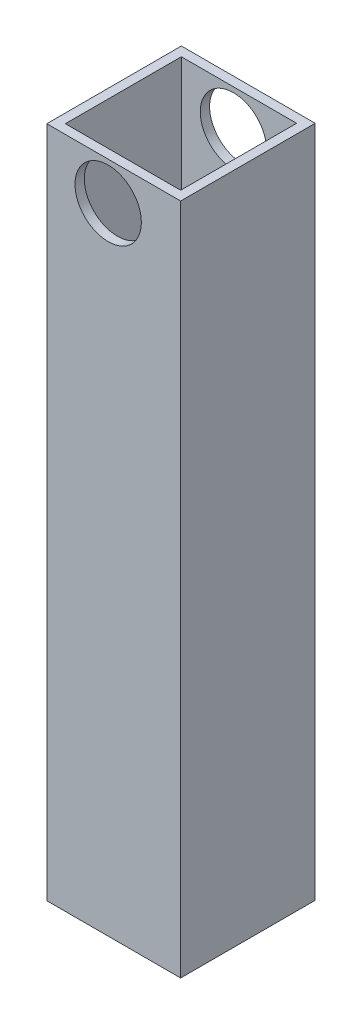
SolidWorks part; units mm, degrees
ref_plane "Front Plane" through (0, 0, 0) normal (0, 0, 1) x (1, 0, 0)
ref_plane "Top Plane" through (0, 0, 0) normal (0, 1, 0) x (1, 0, 0)
ref_plane "Right Plane" through (0, 0, 0) normal (1, 0, 0) x (0, 0, -1)
sketch "Sketch6" plane through (0, 0, 0) normal (0, 1, 0) x (1, 0, 0)
  line L0 (0, 0) -> (25.2621, 0)
  line L1 (25.2621, 0) -> (25.2621, 25.4)
  line L2 (25.2621, 25.4) -> (0, 25.4)
  line L3 (0, 25.4) -> (0, 0)
  dimension "D1" = 25.4
extrude "Boss-Extrude3" add sketch "Sketch6" along normal blind 127 contours L3 L0 L1 L2
sketch "Sketch8" plane through (0, 0, 0) normal (0, 0, 1) x (1, 0, 0)
  circle A1 centre (11.5872, 119.7801) radius 6.263
extrude "Cut-Extrude1" cut sketch "Sketch8" against normal blind 25.4
sketch "Sketch9" plane through (0, 0, 0) normal (0, -1, 0) x (-1, 0, 0)
  line L0 (0, 25.4) -> (0, 0) construction
  line L1 (-1.7526, 23.6474) -> (-23.5095, 23.6474)
  line L2 (-1.7526, 23.6474) -> (-1.7526, 1.7526)
  line L3 (-1.7526, 1.7526) -> (-23.5095, 1.7526)
  line L4 (-23.5095, 23.6474) -> (-23.5095, 1.7526)
  line L5 (-1.7526, 23.6474) -> (-23.5095, 1.7526) construction
  line L6 (-1.7526, 1.7526) -> (-23.5095, 23.6474) construction
  line L7 (-25.2621, 0) -> (-25.2621, 25.4) construction
  line L8 (-17.8502, 0) -> (-5.3242, 0) construction
  line L9 (-25.2621, 25.4) -> (0, 25.4) construction
  point P0 (-12.6311, 12.7)
  dimension "D1" = 1.7526
  dimension "D2" = 1.7526
  dimension "D3" = 1.7526
  dimension "D4" = 1.7526
extrude "Cut-Extrude2" cut sketch "Sketch9" against normal blind 127 contours L2 L1 L4 L3
